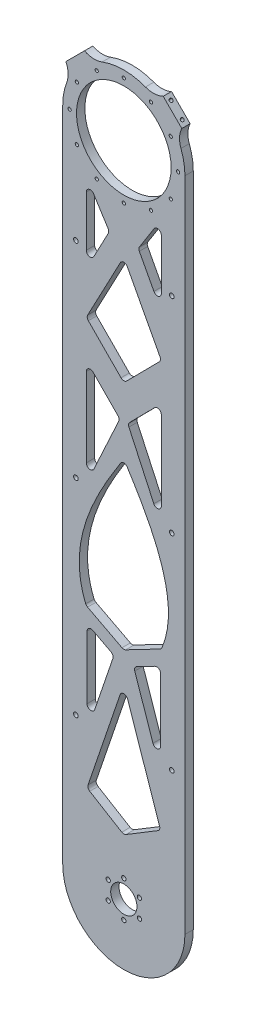
SolidWorks part; units mm, degrees
material "1060 Alloy"
ref_plane "Front Plane" through (0, 0, 0) normal (0, 0, 1) x (1, 0, 0)
ref_plane "Top Plane" through (0, 0, 0) normal (0, 1, 0) x (1, 0, 0)
ref_plane "Right Plane" through (0, 0, 0) normal (1, 0, 0) x (0, 0, -1)
sketch "Sketch2" plane through (0, 0, 0) normal (0, 0, 1) x (1, 0, 0)
  line L0 (0, 0) -> (0, 500) construction
  line L1 (-46.5, 0) -> (-46.5, 500)
  line L2 (46.5, 0) -> (46.5, 500)
  arc A0 (-46.5, 0) -> (46.5, 0) centre (0, 0) ccw
  arc A1 (46.5, 500) -> (-46.5, 500) centre (0, 500) ccw
  circle A2 centre (0, 500) radius 37.25 construction
  circle A3 centre (0, 0) radius 10
  circle A4 centre (0, 13.75) radius 1.65
  circle A5 centre (0, 0) radius 13.75 construction
  circle A6 centre (11.9078, 6.875) radius 1.65
  circle A7 centre (11.9078, -6.875) radius 1.65
  circle A8 centre (0, -13.75) radius 1.65
  circle A9 centre (-11.9078, -6.875) radius 1.65
  circle A10 centre (-11.9078, 6.875) radius 1.65
  point P3 (0, 250)
  point P27 (0, 0)
  dimension "D2" = 74.5
  dimension "D4" = 20
  dimension "D5" = 3.3
  dimension "D6" = 27.5
  dimension "D3" = 46.5
  dimension "D1" = 500
  dimension "D7" = 6
extrude "Boss-Extrude1" add sketch "Sketch2" along normal blind 6.35
sketch "Sketch4" plane through (0, 0, 6.35) normal (0, 0, 1) x (1, 0, 0)
  line L0 (0, 500) -> (0, 999.1647) construction
  line L29 (46.5, 500) -> (-46.5, 500) construction
  line L31 (28.0053, 59.376) -> (0, 42.4117)
  line L32 (0, 141.6934) -> (28.0053, 59.376)
  line L33 (-28.0053, 59.376) -> (0, 141.6934)
  line L34 (0, 42.4117) -> (-28.0053, 59.376)
  line L35 (-7.5, 156.9059) -> (-28.0053, 96.6336)
  line L36 (-28.0053, 167.5829) -> (-7.5, 156.9059)
  line L37 (-28.0053, 96.6336) -> (-28.0053, 167.5829)
  line L38 (28.0053, 167.5829) -> (7.5, 156.9059)
  line L39 (28.0053, 96.6336) -> (28.0053, 167.5829)
  line L40 (7.5, 156.9059) -> (28.0053, 96.6336)
  line L41 (0, 164.2751) -> (28.5505, 179.1412)
  line L42 (0, 164.2751) -> (-28.5505, 179.1412)
  line L43 (28.5505, 259.5868) -> (3, 314.9383)
  line L44 (28.5505, 340.7931) -> (28.5505, 259.5868)
  line L45 (3, 314.9383) -> (28.5505, 340.7931)
  line L46 (-3, 314.9383) -> (-28.5505, 340.7931)
  line L47 (-28.5505, 259.5868) -> (-3, 314.9383)
  line L48 (-28.5505, 340.7931) -> (-28.5505, 259.5868)
  line L49 (0, 423.1428) -> (-28.5505, 369.2462)
  line L50 (-28.5505, 369.2462) -> (0, 340.3557)
  line L51 (0, 340.3557) -> (28.5505, 369.2462)
  line L52 (0, 423.1428) -> (28.5505, 369.2462)
  line L53 (-28.5505, 462.0952) -> (-28.5505, 401.2902)
  line L54 (-11, 434.4215) -> (-28.5505, 462.0952)
  line L55 (-28.5505, 401.2902) -> (-11, 434.4215)
  line L56 (28.5505, 401.2902) -> (11, 434.4215)
  line L57 (28.5505, 462.0952) -> (28.5505, 401.2902)
  line L58 (11, 434.4215) -> (28.5505, 462.0952)
  arc A0 (46.5, 500) -> (-46.5, 500) centre (0, 500) ccw construction
  arc A1 (46.5, 500) -> (-46.5, 500) centre (0, 500) ccw construction
  spline S2 degree 3 poles (28.5505, 179.1412) (45.3203, 216.9857) (19.4301, 259.7903) (0, 290.0258) knots 0 0 0 0 1 1 1 1
  spline S3 degree 3 poles (-28.5505, 179.1412) (-45.3203, 216.9857) (-19.4301, 259.7903) (0, 290.0258) knots 0 0 0 0 1 1 1 1
extrude "Cut-Extrude1" cut sketch "Sketch4" against normal blind 10
fillet "Fillet3" radius 3 30 edges at (-11, 434.4215, 3.175) (-28.5505, 401.2902, 3.175) (28.5505, 401.2902, 3.175) (11, 434.4215, 3.175) (28.5505, 462.0952, 3.175) (-28.5505, 462.0952, 3.175) (0, 423.1428, 3.175) (-28.5505, 369.2462, 3.175) (28.5505, 369.2462, 3.175) (0, 340.3557, 3.175) (28.5505, 340.7931, 3.175) (-28.5505, 340.7931, 3.175) (-3, 314.9383, 3.175) (3, 314.9383, 3.175) (28.5505, 259.5868, 3.175) (-28.5505, 259.5868, 3.175) (28.5505, 179.1412, 3.175) (0, 290.0258, 3.175) (-28.5505, 179.1412, 3.175) (0, 164.2751, 3.175) (-28.0053, 96.6336, 3.175) (28.0053, 96.6336, 3.175) (7.5, 156.9059, 3.175) (-28.0053, 167.5829, 3.175) (28.0053, 167.5829, 3.175) (0, 141.6934, 3.175) (28.0053, 59.376, 3.175) (-28.0053, 59.376, 3.175) (0, 42.4117, 3.175) (-7.5, 156.9059, 3.175)
sketch "Sketch5" plane through (0, 0, 6.35) normal (0, 0, 1) x (1, 0, 0)
  line L0 (0, -46.5) -> (108.8395, -46.5) construction
  line L1 (46.5, 100) -> (-46.5, 100) construction
  line L2 (46.5, 0) -> (46.5, 500) construction
  line L3 (-46.5, 500) -> (-46.5, 0) construction
  line L4 (-46.5, 106.35) -> (46.5, 106.35) construction
  line L5 (36.5, 106.35) -> (36.5, 100) construction
  line L6 (0, 106.35) -> (0, 100) construction
  line L7 (-46.5, 256.35) -> (46.5, 256.35) construction
  line L8 (-46.5, 181.35) -> (46.5, 181.35) construction
  line L9 (-46.5, 337.7) -> (46.5, 337.7) construction
  arc A1 (-46.5, 0) -> (46.5, 0) centre (0, 0) ccw construction
  circle A2 centre (36.5, 103.175) radius 1.75
  circle A3 centre (-36.5, 103.175) radius 1.75
  circle A4 centre (36.5, 259.525) radius 1.75
  circle A5 centre (-36.5, 259.525) radius 1.75
  circle A6 centre (36.5, 415.875) radius 1.75
  circle A7 centre (-36.5, 415.875) radius 1.75
  point P18 (36.5, 103.175)
  dimension "D2" = 3.5
  dimension "D1" = 146.5
  dimension "D3" = 10
  dimension "D4" = 6.35
  dimension "D5" = 150
  dimension "D6" = 81.35
  dimension "D7" = 81.35
extrude "Cut-Extrude2" cut sketch "Sketch5" against normal through all
sketch "Sketch6" plane through (0, 0, 6.35) normal (0, 0, 1) x (1, 0, 0)
  circle A0 centre (0, 500) radius 26.5
  arc A1 (46.5, 500) -> (-46.5, 500) centre (0, 500) ccw construction
  arc A2 (46.5, 500) -> (-46.5, 500) centre (0, 500) ccw construction
  dimension "D1" = 20
extrude "Cut-Extrude3" cut sketch "Sketch6" against normal blind 10
sketch "Sketch7" plane through (0, 0, 6.35) normal (0, 0, 1) x (1, 0, 0)
  line L1 (40.0163, 523.6842) -> (44.1104, 529.9682) construction
  line L2 (23.6842, 540.0163) -> (29.9682, 544.1104) construction
  line L3 (44.1104, 529.9682) -> (29.9682, 544.1104)
  line L4 (0, 500) -> (37.0393, 537.0393) construction
  line L5 (0, 500) -> (0, 546.5) construction
  arc A0 (46.5, 500) -> (-46.5, 500) centre (0, 500) ccw construction
  arc A1 (29.9682, 544.1104) -> (16.4747, 543.4837) centre (22.4977, 559.381) cw
  arc A2 (44.1104, 529.9682) -> (43.4837, 516.4747) centre (59.381, 522.4977) ccw
  arc A3 (16.4747, 543.4837) -> (43.4837, 516.4747) centre (0, 500) cw
  dimension "D3" = 17
  dimension "D5" = 17
  dimension "D1" = 20
  dimension "D2" = 7.5
  dimension "D4" = 8
  dimension "D6" = 8
  dimension "D7" = 45
extrude "Boss-Extrude2" add sketch "Sketch7" against normal up to surface (6.35 mm away) up to face at (26.5, 500, 0)
sketch "Sketch8" plane through (287.0393, 287.0393, 0) normal (0.7071, 0.7071, 0) x (0, 0, -1)
  line L0 (0, 363.5534) -> (-6.35, 363.5534) construction
  line L1 (0, 343.5534) -> (-6.35, 343.5534) construction
  line L2 (-6.35, 343.5534) -> (-6.35, 363.5534) construction
  point P0 (-3.175, 359.5534)
  point P1 (-3.175, 347.5534)
  dimension "D1" = 4
  dimension "D2" = 4
  dimension "D3" = 3.175
hole_wizard "Tap Drill for M3x0.5 Tap1" positions "Sketch8" profile "Sketch9" hole size "M3x0.5" standard "ANSI Metric"
sketch "Sketch9" plane through (32.7967, 541.282, 3.175) normal (0, 0, 1) x (-0.7071, 0.7071, 0)
  line L0 (0, 0) -> (0, 5.7511)
  line L1 (0, 5.7511) -> (1.25, 5)
  line L2 (1.25, 5) -> (1.25, 0)
  line L5 (1.25, 0) -> (0, 0)
  line L10 (0, 5.7511) -> (-1.25, 5) construction
  line L11 (0, -6.35) -> (0, 107.95) construction
  dimension "Hole Dia." = 2.5
  dimension "Hole Depth" = 5
  dimension "Drill Angle" = 118
pattern_circular "CirPattern2" count 2 every 90 about axis through (0, 500, 0) along (0, 0, 1) of "Boss-Extrude2", "Tap Drill for M3x0.5 Tap1"
sketch "Sketch11" plane through (0, 0, 6.35) normal (0, 0, 1) x (1, 0, 0)
  circle A0 centre (0, 500) radius 36
  circle A1 centre (0, 500) radius 26.5 construction
  dimension "D1" = 72
extrude "Cut-Extrude5" cut sketch "Sketch11" against normal through all
sketch "Sketch12" plane through (0, 0, 6.35) normal (0, 0, 1) x (1, 0, 0)
  circle A15 centre (0, 500) radius 41.25 construction
  circle A16 centre (0, 500) radius 36 construction
  circle A17 centre (0, 500) radius 36 construction
  circle A18 centre (0, 541.25) radius 1.25
  dimension "D1" = 82.5
  dimension "D2" = 2.5
extrude "Cut-Extrude6" cut sketch "Sketch12" against normal through all both and the other way through all
pattern_circular "CirPattern3" count 12 over 360 about axis through (0, 500, 0) along (0, 0, 1) of "Cut-Extrude6"
equation "\"L1L\"=500"
equation "\"L1Thick\"=6.35"
equation "\"D1@Sketch2\"=\"L1L\""
equation "\"Harm-Drive-Outer\"=74.5"
equation "\"D2@Sketch2\"=\"Harm-Drive-Outer\""
equation "\"D1@Boss-Extrude1\"=\"L1Thick\""
